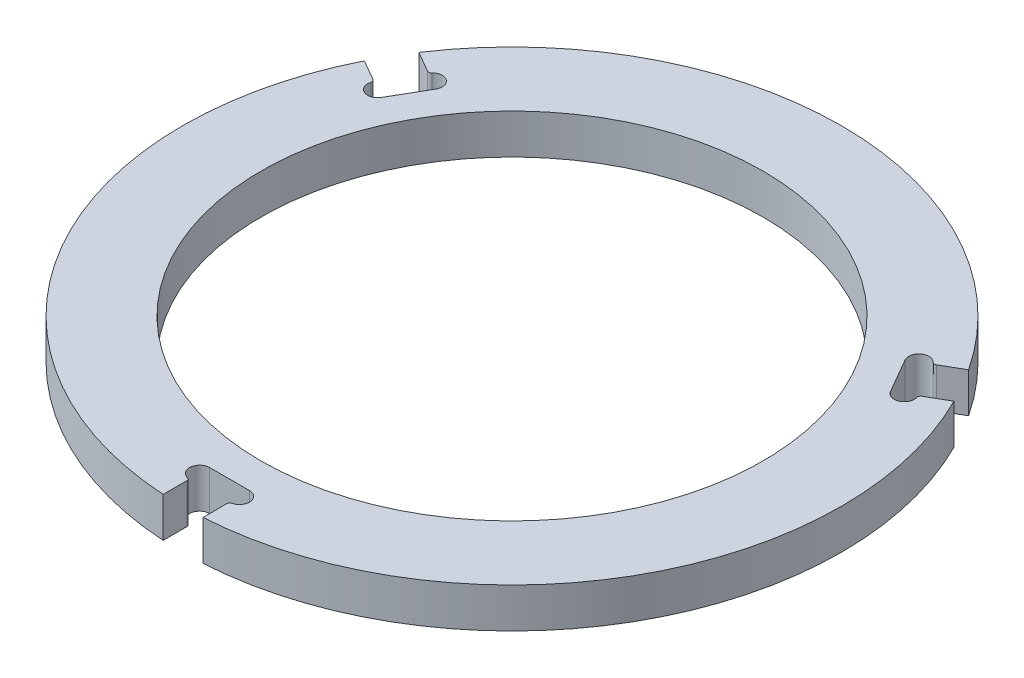
SolidWorks part; units mm, degrees
ref_plane "Front Plane" through (0, 0, 0) normal (0, 0, 1) x (1, 0, 0)
ref_plane "Top Plane" through (0, 0, 0) normal (0, 1, 0) x (1, 0, 0)
ref_plane "Right Plane" through (0, 0, 0) normal (1, 0, 0) x (0, 0, -1)
sketch "Sketch1" plane through (0, 0, 0) normal (0, 1, 0) x (1, 0, 0)
  circle A0 centre (0, 0) radius 80
  circle A1 centre (0, 0) radius 105
  dimension "D1" = 160
  dimension "D2" = 25
extrude "Boss-Extrude1" add sketch "Sketch1" along normal blind 12.7
sketch "Sketch2" plane through (0, 12.7, 0) normal (0, 1, 0) x (1, 0, 0)
  line L0 (0, 0) -> (0, -105) construction
  line L1 (6.35, -105) -> (-6.35, -105)
  line L2 (-6.35, -105) -> (-6.35, -90) construction
  line L3 (-6.35, -90) -> (6.35, -90)
  line L4 (6.35, -90) -> (6.35, -105) construction
  line L5 (0, -80) -> (0, -90) construction
  line L6 (6.35, -96.4) -> (6.35, -105)
  line L7 (-6.35, -96.4) -> (-6.35, -105)
  circle A0 centre (0, 0) radius 105 construction
  circle A1 centre (0, 0) radius 80 construction
  arc A2 (-6.35, -90) -> (-6.35, -96.4) centre (-6.35, -93.2) ccw
  arc A3 (6.35, -96.4) -> (6.35, -90) centre (6.35, -93.2) ccw
  point P8 (0, -105)
  dimension "D3" = 6.4
  dimension "D1" = 10
  dimension "D2" = 12.7
extrude "Cut-Extrude1" cut sketch "Sketch2" against normal through all
fillet "Fillet1" radius 1 2 edges at (6.35, 6.35, 96.4) (-6.35, 6.35, 96.4)
pattern_circular "CirPattern1" count 3 over 360 about axis through (0, 0, 0) along (0, 1, 0) of "Cut-Extrude1", "Fillet1"
